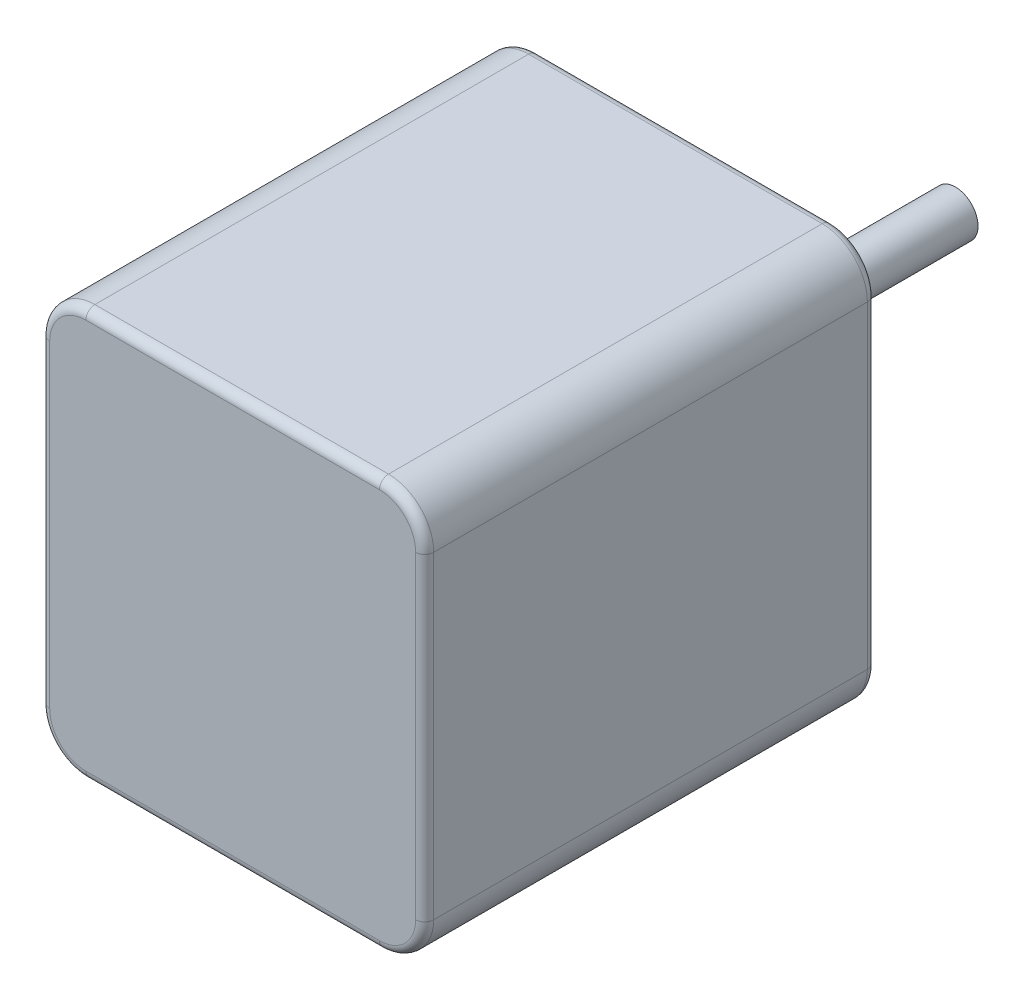
SolidWorks part; units mm, degrees
ref_plane "Plan de face" through (0, 0, 0) normal (0, 0, 1) x (1, 0, 0)
ref_plane "Plan de dessus" through (0, 0, 0) normal (0, 1, 0) x (1, 0, 0)
ref_plane "Plan de droite" through (0, 0, 0) normal (1, 0, 0) x (0, 0, -1)
sketch "Esquisse1" plane through (0, 0, 0) normal (0, 0, 1) x (1, 0, 0)
  line L1 (-21.25, -22.6105) -> (21.25, -22.6105)
  line L2 (-21.25, -22.6105) -> (-21.25, 22.6105)
  line L3 (-21.25, 22.6105) -> (21.25, 22.6105)
  line L4 (21.25, -22.6105) -> (21.25, 22.6105)
  line L5 (-21.25, -22.6105) -> (21.25, 22.6105) construction
  line L6 (-21.25, 22.6105) -> (21.25, -22.6105) construction
  point P0 (0, 0)
  dimension "D1" = 42.5
extrude "Boss.-Extru.1" add sketch "Esquisse1" along normal blind 50
sketch "Esquisse2" plane through (0, 0, 0) normal (0, 0, -1) x (-1, 0, 0)
  circle A0 centre (0, 0) radius 2.5
  dimension "D1" = 5
extrude "Boss.-Extru.2" add sketch "Esquisse2" along normal blind 30
fillet "Congé1" radius 5 4 edges at (-21.25, 22.6105, 25) (-21.25, -22.6105, 25) (21.25, -22.6105, 25) (21.25, 22.6105, 25)
fillet "Congé2" radius 1 8 edges at (19.7855, 21.146, 50) (21.25, 0, 50) (19.7855, -21.146, 50) (0, -22.6105, 50) (-19.7855, -21.146, 50) (-21.25, 0, 50) (-19.7855, 21.146, 50) (0, 22.6105, 50)
fillet "Congé3" radius 1 8 edges at (19.7855, 21.146, 0) (0, 22.6105, 0) (-19.7855, 21.146, 0) (-21.25, 0, 0) (-19.7855, -21.146, 0) (0, -22.6105, 0) (19.7855, -21.146, 0) (21.25, 0, 0)
